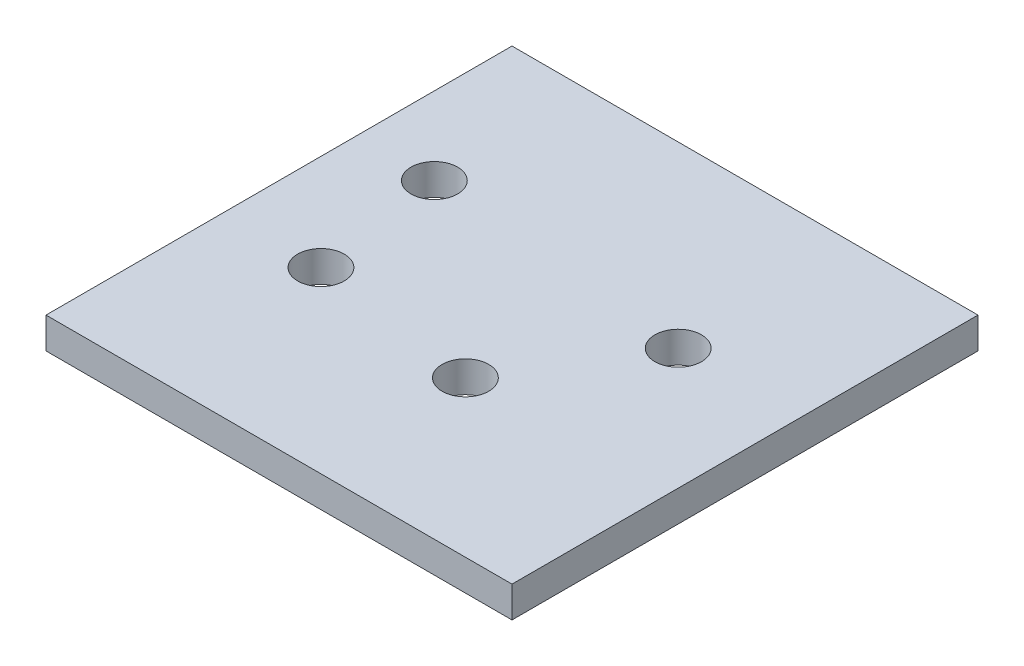
SolidWorks part; units mm, degrees
ref_plane "前视基准面" through (0, 0, 0) normal (0, 0, 1) x (1, 0, 0)
ref_plane "上视基准面" through (0, 0, 0) normal (0, 1, 0) x (1, 0, 0)
ref_plane "右视基准面" through (0, 0, 0) normal (1, 0, 0) x (0, 0, -1)
sketch "草图1" plane through (0, 0, 0) normal (0, 1, 0) x (1, 0, 0)
  line L0 (-23.6293, 2.4784) -> (6.3707, 2.4784)
  line L1 (-23.6293, 17.4784) -> (6.3707, 17.4784)
  line L2 (-23.6293, 17.4784) -> (-23.6293, -12.5216)
  line L3 (-23.6293, -12.5216) -> (6.3707, -12.5216)
  line L4 (6.3707, 17.4784) -> (6.3707, -12.5216)
  circle A0 centre (-17.4293, -1.0216) radius 1.5
  circle A1 centre (-6.6293, -2.5216) radius 1.5
  circle A2 centre (-18.6293, 7.4784) radius 1.5
  circle A3 centre (-1.4293, 5.9784) radius 1.5
  point P14 (0, 0)
  dimension "D3" = 3
  dimension "D4" = 3
  dimension "D6" = 3
  dimension "D7" = 3
  dimension "D1" = 30
  dimension "D2" = 30
  dimension "D5" = 10.8
  dimension "D8" = 17.2
  dimension "D9" = 10
  dimension "D10" = 7
  dimension "D11" = 3.5
  dimension "D12" = 5
  dimension "D13" = 5
  dimension "D14" = 5.2
extrude "凸台-拉伸1" add sketch "草图1" along normal blind 2 contours L4 L0 L2 L3 A1 A0 | A0 | L4 L1 L2 L0 A3 A2
